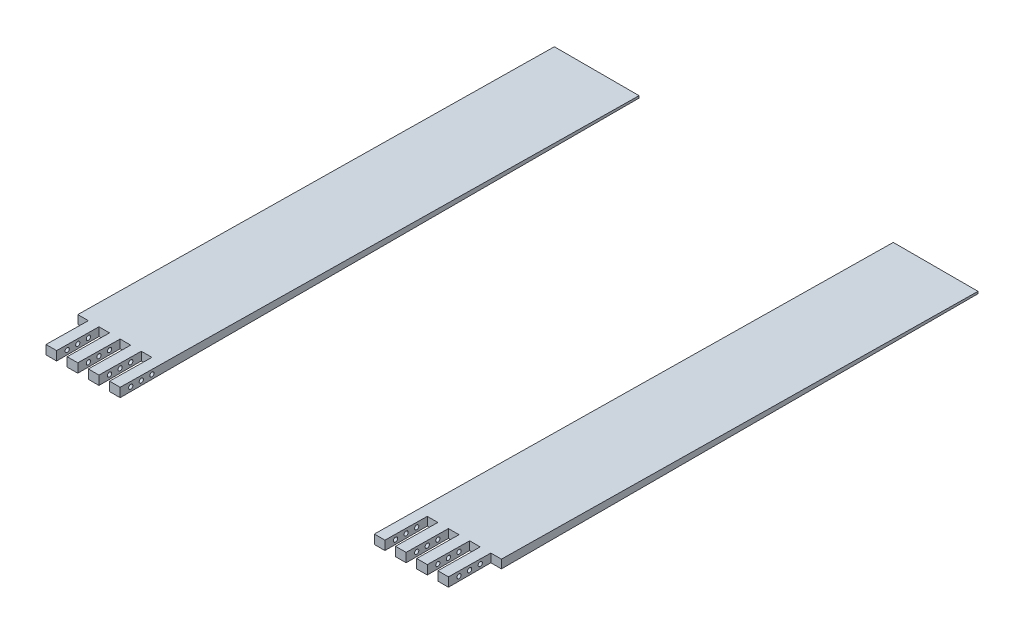
SolidWorks part; units mm, degrees
ref_plane "前视基准面" through (0, 0, 0) normal (0, 0, 1) x (1, 0, 0)
ref_plane "上视基准面" through (0, 0, 0) normal (0, 1, 0) x (1, 0, 0)
ref_plane "右视基准面" through (0, 0, 0) normal (1, 0, 0) x (0, 0, -1)
sketch "草图1" plane through (0, 0, 0) normal (0, 1, 0) x (1, 0, 0)
  line L1 (-100, -20) -> (100, -20)
  line L2 (-100, -20) -> (-100, 20)
  line L3 (-100, 20) -> (100, 20)
  line L4 (100, -20) -> (100, 20)
  line L5 (-100, -20) -> (100, 20) construction
  line L6 (-100, 20) -> (100, -20) construction
  line L7 (100, -20) -> (60, -20)
  line L8 (100, -20) -> (100, 455)
  line L9 (100, 455) -> (60, 455)
  line L10 (60, -20) -> (60, 455)
  line L11 (-100, -20) -> (-60, -20)
  line L12 (-100, -20) -> (-100, 455)
  line L13 (-100, 455) -> (-60, 455)
  line L14 (-60, -20) -> (-60, 455)
  point P0 (0, 0)
  dimension "D1" = 200
  dimension "D2" = 40
  dimension "D3" = 475
  dimension "D4" = 475
  dimension "D5" = 40
  dimension "D6" = 40
extrude "凸台-拉伸1" add sketch "草图1" along normal blind 5 contours L3 L14 L13 L12 | L1 L14 L3 L2 | L14 L1 L10 L3 | L10 L1 L4 L3 | L10 L3 L8 L9
sketch "草图2" plane through (100, 0, 0) normal (1, 0, 0) x (0, 0, -1)
  line L0 (455, 0) -> (455, 5)
  line L1 (455, 5) -> (155, 5)
  line L2 (-20, 5) -> (455, 5) construction
  line L3 (155, 5) -> (455, 1)
  line M4 (455, 5) -> (-20, 5)
  dimension "D1" = 1
  dimension "D2" = 300
extrude "切除-拉伸2" cut sketch "草图2" against normal through all contours L3 L0 M4
sketch "草图3" plane through (0, 5, 0) normal (0, 1, 0) x (1, 0, 0)
  line L0 (100, 155) -> (100, 455) construction
  line L1 (-100, -20) -> (100, -20)
  line L2 (-100, -20) -> (-100, 230)
  line L3 (-100, 230) -> (100, 230)
  line L4 (100, -20) -> (100, 230)
  line L5 (-100, 230) -> (-95, 230)
  line L6 (-95, 230) -> (-95, 210)
  line L7 (-95, 210) -> (-90, 210)
  line L8 (-90, 210) -> (-90, 230)
  line L9 (-90, 230) -> (-85, 230)
  line L10 (-85, 230) -> (-85, 210)
  line L11 (-85, 210) -> (-80, 210)
  line L12 (-60, 455) -> (-60, 155) construction
  line L13 (-60, 210) -> (-60, 230)
  line L14 (100, 230) -> (75, 230)
  line L15 (75, 230) -> (75, 210)
  line L16 (75, 210) -> (70, 210)
  line L17 (70, 210) -> (70, 230)
  line L18 (70, 230) -> (65, 230)
  line L19 (65, 230) -> (65, 210)
  line L20 (65, 210) -> (60, 210)
  line L21 (60, 455) -> (60, 155) construction
  line L22 (60, 210) -> (60, 230)
  line L23 (-100, 230) -> (-100, 455)
  line L24 (-100, 455) -> (100, 455)
  line L25 (100, 455) -> (100, 230)
  line L26 (-80, 210) -> (-80, 230)
  line L27 (-80, 230) -> (-75, 230)
  line L28 (-75, 230) -> (-75, 210)
  line L29 (-75, 210) -> (-70, 210)
  line L30 (-70, 210) -> (-70, 230)
  line L31 (-70, 230) -> (-65, 230)
  line L32 (-65, 230) -> (-65, 210)
  line L33 (-65, 210) -> (-60, 210)
  line L34 (75, 230) -> (80, 230)
  line L35 (80, 230) -> (80, 210)
  line L36 (80, 210) -> (85, 210)
  line L37 (85, 210) -> (85, 230)
  line L38 (85, 230) -> (90, 230)
  line L39 (90, 230) -> (90, 210)
  line L40 (90, 210) -> (95, 210)
  line L41 (95, 210) -> (95, 230)
  line M14 (-60, 155) -> (-100, 155)
  line M15 (-100, 155) -> (-100, -20)
  line M16 (-100, -20) -> (100, -20)
  line M17 (100, -20) -> (100, 155)
  line M18 (100, 155) -> (60, 155)
  line M19 (60, 155) -> (60, 20)
  line M20 (60, 20) -> (-60, 20)
  line M21 (-60, 20) -> (-60, 155)
  dimension "D1" = 250
  dimension "D2" = 5
  dimension "D3" = 5
  dimension "D4" = 5
  dimension "D5" = 5
  dimension "D6" = 5
  dimension "D7" = 5
  dimension "D8" = 20
  dimension "D9" = 20
  dimension "D10" = 5
  dimension "D11" = 5
  dimension "D12" = 5
  dimension "D13" = 5
  dimension "D14" = 5
  dimension "D15" = 5
  dimension "D16" = 5
  dimension "D17" = 5
extrude "切除-拉伸3" cut sketch "草图3" against normal through all contours M21 M14 M15 M16 M17 M18 M19 M20 | L41 L40 L39 L3 L37 L36 L35 L15 L16 L17 L19 L20 L22 L13 L33 L32 L30 L29 L28 L26 L11 L10 L8 L7 L6 L2 L4 M14 M21 M20 M19 M18
sketch "草图4" plane through (100, 0, 0) normal (1, 0, 0) x (0, 0, -1)
  line L0 (230, 0) -> (230, 4) construction
  line L1 (210, 0) -> (230, 0) construction
  circle A0 centre (225, 2) radius 1
  circle A1 centre (220, 2) radius 1
  circle A2 centre (215, 2) radius 1
  dimension "D1" = 2
  dimension "D2" = 2
  dimension "D3" = 2
  dimension "D4" = 5
  dimension "D5" = 5
  dimension "D6" = 5
  dimension "D7" = 2
  dimension "D8" = 2
  dimension "D9" = 2
extrude "切除-拉伸4" cut sketch "草图4" against normal through all
